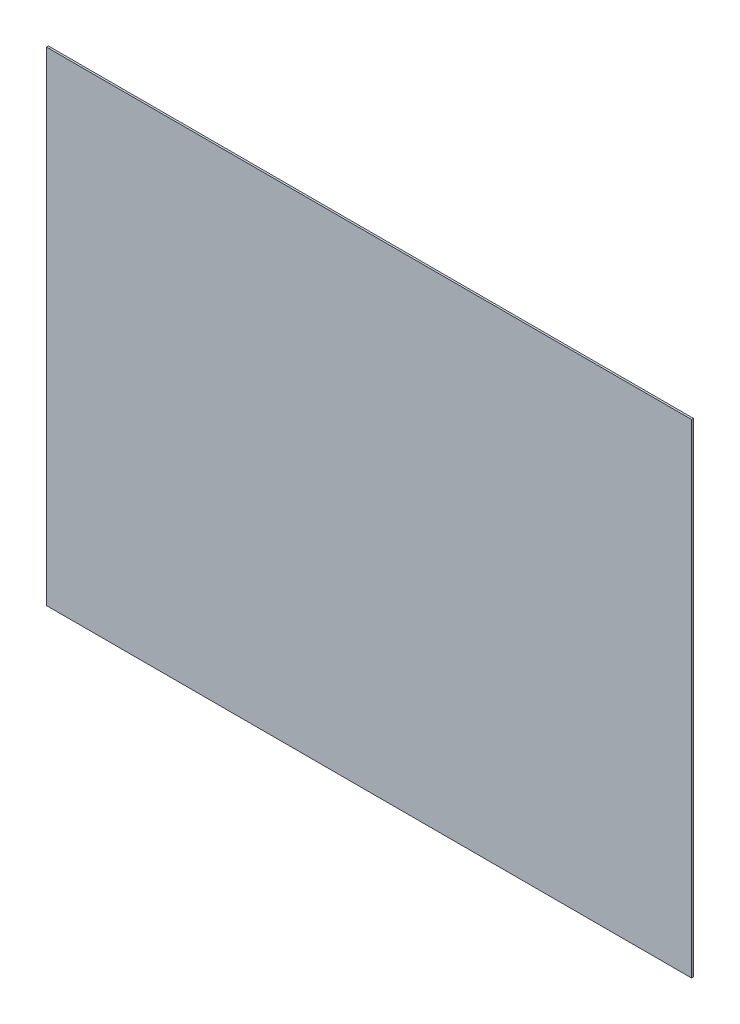
SolidWorks part; units mm, degrees
ref_plane "Plan de face" through (0, 0, 0) normal (0, 0, 1) x (1, 0, 0)
ref_plane "Plan de dessus" through (0, 0, 0) normal (0, 1, 0) x (1, 0, 0)
ref_plane "Plan de droite" through (0, 0, 0) normal (1, 0, 0) x (0, 0, -1)
sketch "Esquisse1" plane through (0, 0, 0) normal (0, 0, 1) x (1, 0, 0)
  line L1 (-200, 150) -> (200, 150)
  line L2 (-200, 150) -> (-200, -150)
  line L3 (-200, -150) -> (200, -150)
  line L4 (200, 150) -> (200, -150)
  line L5 (-200, 150) -> (200, -150) construction
  line L6 (-200, -150) -> (200, 150) construction
  point P0 (0, 0)
  dimension "D1" = 300
  dimension "D2" = 400
extrude "Boss.-Extru.1" add sketch "Esquisse1" along normal blind 1.2
